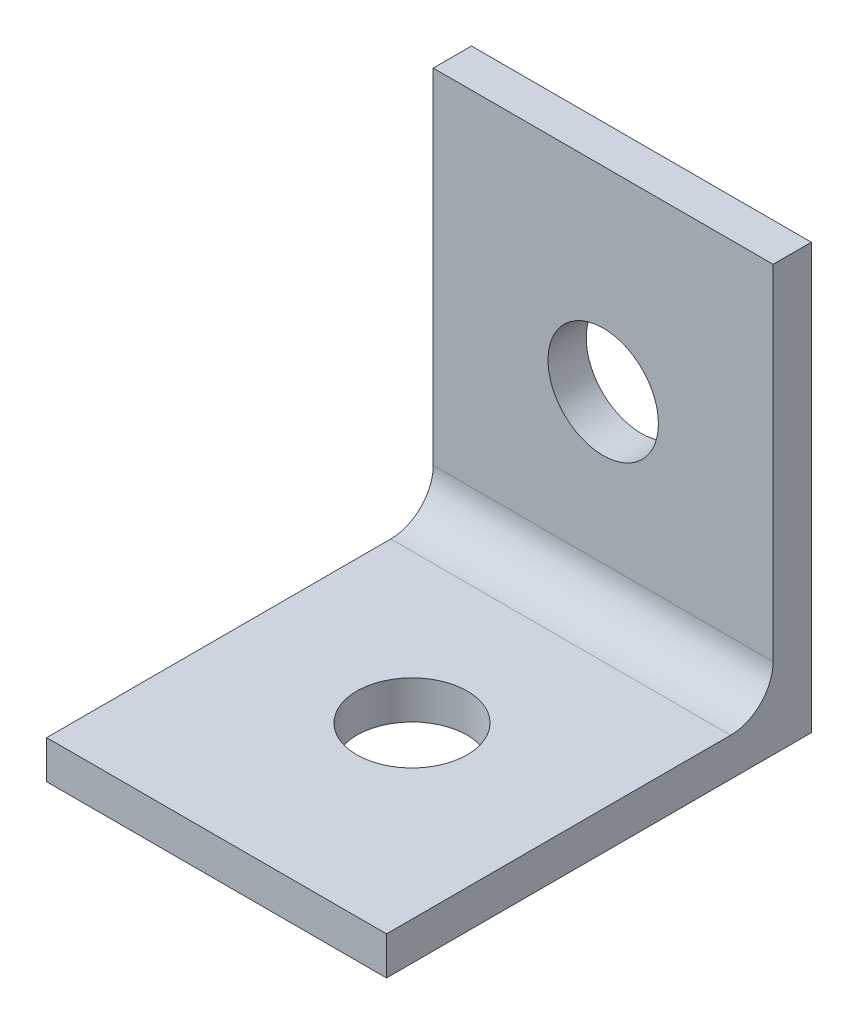
SolidWorks part; units mm, degrees
ref_plane "Front Plane" through (0, 0, 0) normal (0, 0, 1) x (1, 0, 0)
ref_plane "Top Plane" through (0, 0, 0) normal (0, 1, 0) x (1, 0, 0)
ref_plane "Right Plane" through (0, 0, 0) normal (1, 0, 0) x (0, 0, -1)
sketch "Sketch1" plane through (0, 0, 0) normal (0, 0, 1) x (1, 0, 0)
  line L1 (0, 0) -> (16, 0)
  line L2 (0, 0) -> (0, 20)
  line L3 (0, 20) -> (16, 20)
  line L4 (16, 0) -> (16, 20)
  dimension "D1" = 16
  dimension "D2" = 20
extrude "Boss-Extrude1" add sketch "Sketch1" along normal blind 1.8
sketch "Sketch2" plane through (0, 0, 0) normal (0, -1, 0) x (1, 0, 0)
  line L1 (0, 1.8) -> (16, 1.8)
  line L2 (0, 1.8) -> (0, 20)
  line L3 (0, 20) -> (16, 20)
  line L4 (16, 1.8) -> (16, 20)
  dimension "D1" = 18.2
  dimension "D2" = 16
extrude "Boss-Extrude2" add sketch "Sketch2" against normal blind 1.8
sketch "Sketch3" plane through (0, 0, 1.8) normal (0, 0, 1) x (1, 0, 0)
  line L0 (16, 1.8) -> (16, 20) construction
  line L1 (0, 1.8) -> (16, 1.8) construction
  circle A0 centre (8, 10.8) radius 2.6
  dimension "D1" = 5.2
  dimension "D2" = 8
  dimension "D3" = 9
extrude "Cut-Extrude1" cut sketch "Sketch3" against normal blind 1.8
sketch "Sketch4" plane through (0, 1.8, 0) normal (0, 1, 0) x (1, 0, 0)
  line L0 (16, -1.8) -> (16, -20) construction
  line L2 (0, -1.8) -> (16, -1.8) construction
  circle A0 centre (8, -10.8) radius 2.6
  dimension "D1" = 8
  dimension "D2" = 5.2
  dimension "D3" = 9
extrude "Cut-Extrude2" cut sketch "Sketch4" against normal blind 1.8
fillet "Fillet1" radius 2 1 edges at (8, 1.8, 1.8)
